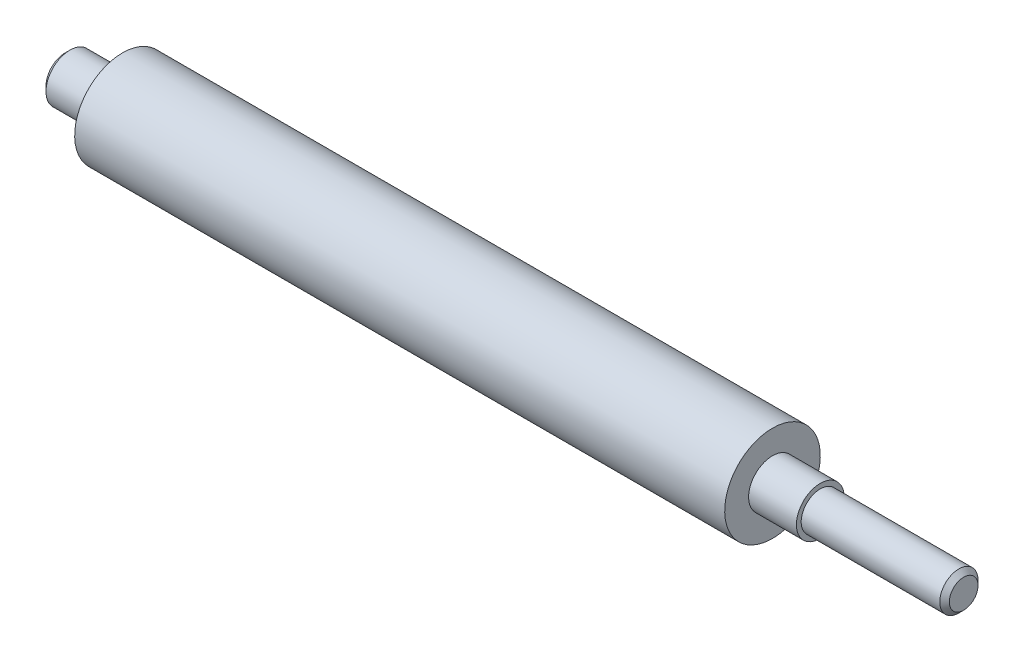
SolidWorks part; units mm, degrees
material "Brass"
ref_plane "Front Plane" through (0, 0, 0) normal (0, 0, 1) x (1, 0, 0)
ref_plane "Top Plane" through (0, 0, 0) normal (0, 1, 0) x (1, 0, 0)
ref_plane "Right Plane" through (0, 0, 0) normal (1, 0, 0) x (0, 0, -1)
sketch "Sketch1" plane through (0, 0, 0) normal (0, 0, 1) x (1, 0, 0)
  line L0 (0, 0) -> (0, 2.5)
  line L1 (0, 2.5) -> (6, 2.5)
  line L2 (6, 2.5) -> (6, 5)
  line L3 (6, 5) -> (74, 5)
  line L4 (74, 5) -> (74, 2.5)
  line L5 (74, 2.5) -> (79, 2.5)
  line L6 (79, 2.5) -> (79, 2)
  line L7 (79, 2) -> (94, 2)
  line L8 (94, 2) -> (94, 0)
  line L9 (94, 0) -> (0, 0)
  dimension "D1" = 2.5
  dimension "D2" = 5
  dimension "D3" = 68
  dimension "D4" = 6
  dimension "D5" = 20
  dimension "D6" = 5
  dimension "D7" = 2
revolve "Revolve1" add sketch "Sketch1" angle 360 about L9
chamfer "Chamfer1" distance 0.5 angle 45 2 edges at (0, 2.5, 0) (94, 2, 0)
